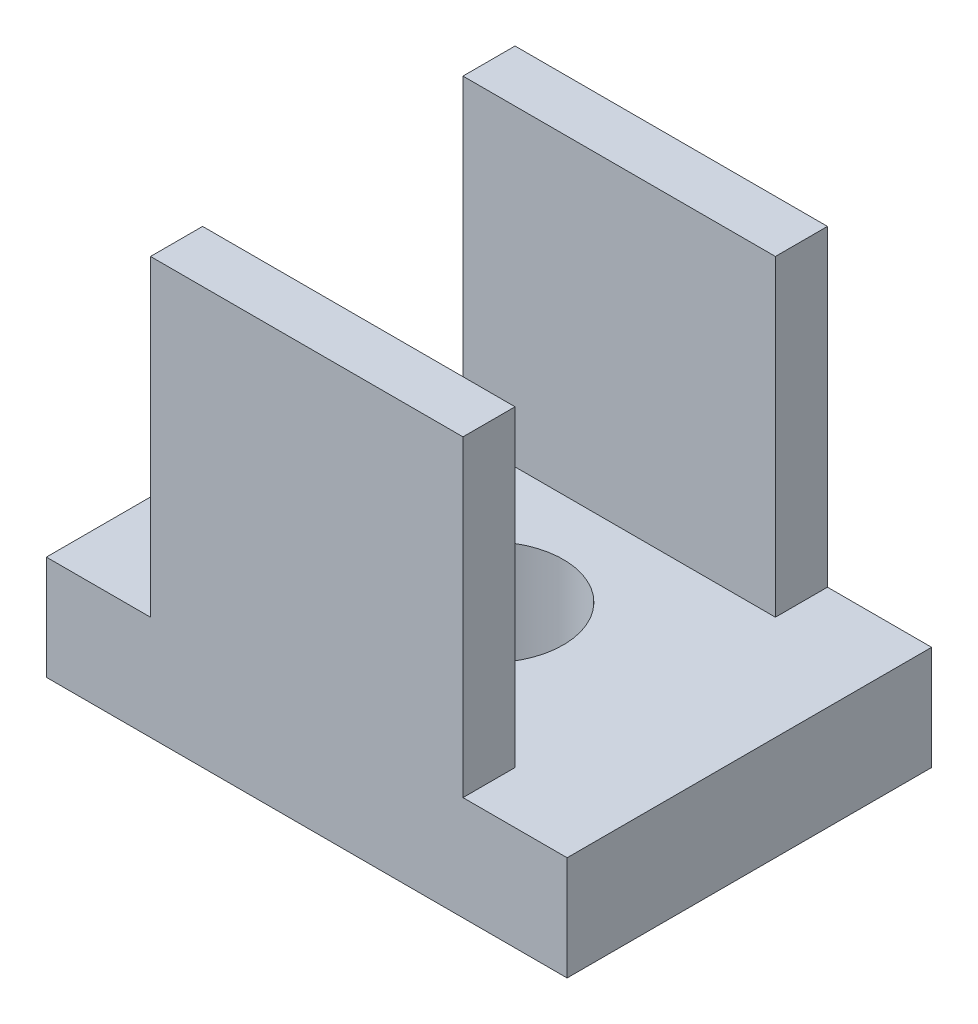
SolidWorks part; units mm, degrees
ref_plane "Front Plane" through (0, 0, 0) normal (0, 0, 1) x (1, 0, 0)
ref_plane "Top Plane" through (0, 0, 0) normal (0, 1, 0) x (1, 0, 0)
ref_plane "Right Plane" through (0, 0, 0) normal (1, 0, 0) x (0, 0, -1)
sketch "Sketch1" plane through (0, 0, 0) normal (0, 1, 0) x (1, 0, 0)
  line L1 (-5, -3.5) -> (5, -3.5)
  line L2 (-5, -3.5) -> (-5, 3.5)
  line L3 (-5, 3.5) -> (5, 3.5)
  line L4 (5, -3.5) -> (5, 3.5)
  line L5 (-5, -3.5) -> (5, 3.5) construction
  line L6 (-5, 3.5) -> (5, -3.5) construction
  point P0 (0, 0)
  dimension "D1" = 10
  dimension "D2" = 7
extrude "Boss-Extrude1" add sketch "Sketch1" along normal blind 2
sketch "Sketch2" plane through (0, 2, 0) normal (0, 1, 0) x (1, 0, 0)
  circle A0 centre (0, 0) radius 1.425
  dimension "D1" = 2.85
extrude "Cut-Extrude1" cut sketch "Sketch2" against normal blind 2
sketch "Sketch4" plane through (0, 2, 0) normal (0, 1, 0) x (1, 0, 0)
  line L0 (5, 3.5) -> (-5, 3.5) construction
  line L3 (-3, 2.5) -> (3, 2.5)
  line L5 (0, 3.5) -> (3, 2.5) construction
  line L6 (-3, 2.5) -> (0, 3.5) construction
  line L7 (-3, 2.5) -> (-3, 3.5)
  line L8 (-3, 3.5) -> (3, 3.5)
  line L9 (3, 3.5) -> (3, 2.5)
  line L10 (0, 0) -> (-5.8276, 0) construction
  line L11 (-5.8276, 0) -> (5.6493, 0) construction
  line L12 (-3, -2.5) -> (0, -3.5) construction
  line L13 (0, -3.5) -> (3, -2.5) construction
  line L14 (3, -3.5) -> (3, -2.5)
  line L15 (-3, -3.5) -> (3, -3.5)
  line L16 (-3, -2.5) -> (-3, -3.5)
  line L17 (-3, -2.5) -> (3, -2.5)
  point P0 (0, 3.5)
  point P2 (-3, 3)
  dimension "D1" = 6
  dimension "D2" = 3
  dimension "D3" = 1
extrude "Boss-Extrude2" add sketch "Sketch4" along normal blind 6
